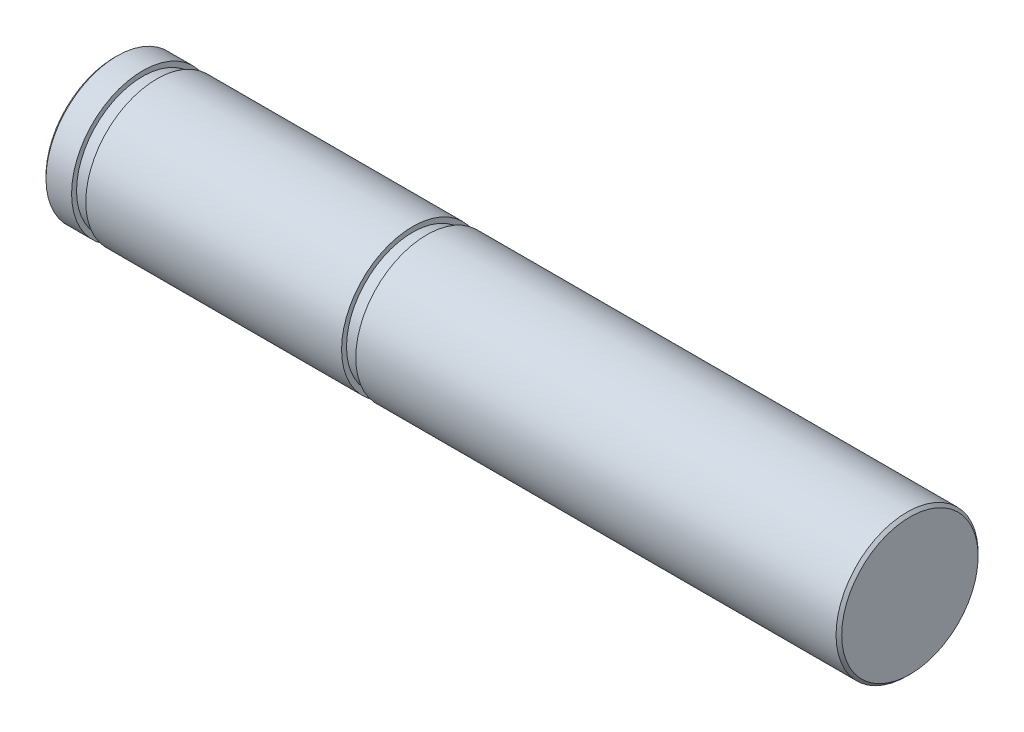
SolidWorks part; units mm, degrees
ref_plane "Front Plane" through (0, 0, 0) normal (0, 0, 1) x (1, 0, 0)
ref_plane "Top Plane" through (0, 0, 0) normal (0, 1, 0) x (1, 0, 0)
ref_plane "Right Plane" through (0, 0, 0) normal (1, 0, 0) x (0, 0, -1)
sketch "Sketch1" plane through (0, 0, 0) normal (0, 0, 1) x (1, 0, 0)
  line L0 (0, 0) -> (0, 5)
  line L1 (0, 5) -> (-34, 5)
  line L2 (-53, 5) -> (-53, 4.65)
  line L3 (-53, 4.65) -> (-54, 4.65)
  line L4 (-54, 4.65) -> (-54, 5)
  line L5 (-54, 5) -> (-56, 5)
  line L6 (-56, 5) -> (-56, 0)
  line L7 (-56, 0) -> (0, 0)
  line L8 (0, 0) -> (5, 0) construction
  line L9 (-35, 5) -> (-35, 4.65)
  line L10 (-35, 4.65) -> (-34, 4.65)
  line L11 (-34, 4.65) -> (-34, 5)
  line L12 (-35, 5) -> (-53, 5)
  dimension "D1" = 10
  dimension "D2" = 1
  dimension "D3" = 9.3
  dimension "D4" = 3
  dimension "D5" = 18
  dimension "D6" = 34
revolve "Revolve1" add sketch "Sketch1" angle 360 about L8
cosmetic thread "Cosmetic Thread1" parameters "D1"=22, "D2"=8.344
chamfer "Chamfer2" distance 0.2 2 edges at (0, 0, 5) (-56, 0, 5)
